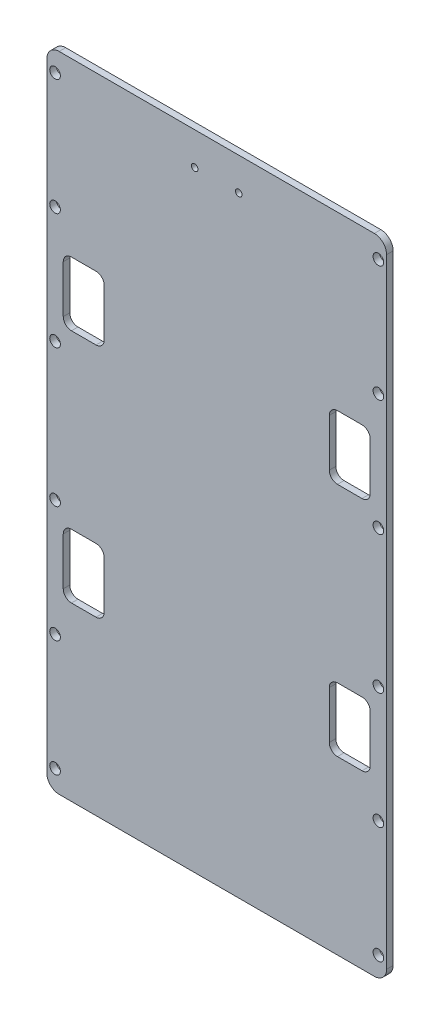
SolidWorks part; units mm, degrees
material "FR4_stuffedProtoboard"
ref_plane "Front Plane" through (0, 0, 0) normal (0, 0, 1) x (1, 0, 0)
ref_plane "Top Plane" through (0, 0, 0) normal (0, 1, 0) x (1, 0, 0)
ref_plane "Right Plane" through (0, 0, 0) normal (1, 0, 0) x (0, 0, -1)
sketch "Sketch1" plane through (0, 0, 0) normal (0, 0, 1) x (1, 0, 0)
  line L0 (-41.5, 0) -> (0, 0) construction
  line L1 (-38.5, 78.6) -> (38.5, 78.6)
  line L2 (-41.5, 75.6) -> (-41.5, -75.6)
  line L3 (-38.5, -78.6) -> (38.5, -78.6)
  line L4 (41.5, 75.6) -> (41.5, -75.6)
  line L5 (0, 0) -> (41.5, 0) construction
  line L6 (6.16, 74.2) -> (0, 70.6)
  line L7 (-35, 74.6) -> (-20.5, 74.6)
  line L8 (-37.5, 72.1) -> (-37.5, 52.1)
  line L9 (-35, 49.6) -> (-20.5, 49.6)
  line L10 (-18, 72.1) -> (-18, 52.1)
  line L11 (-12.5, 74.6) -> (12.5, 74.6)
  line L12 (-15, 72.1) -> (-15, 52.1)
  line L13 (-12.5, 49.6) -> (12.5, 49.6)
  line L14 (15, 72.1) -> (15, 52.1)
  line L15 (20.5, 74.6) -> (35, 74.6)
  line L16 (18, 72.1) -> (18, 52.1)
  line L17 (20.5, 49.6) -> (35, 49.6)
  line L18 (37.5, 72.1) -> (37.5, 52.1)
  line L19 (-35, 46.6) -> (-20.5, 46.6)
  line L20 (-37.5, 44.1) -> (-37.5, 21.1)
  line L21 (-35, 18.6) -> (-20.5, 18.6)
  line L22 (-18, 44.1) -> (-18, 21.1)
  line L23 (-12.5, 46.6) -> (12.5, 46.6)
  line L24 (-15, 44.1) -> (-15, 21.1)
  line L25 (-12.5, 18.6) -> (12.5, 18.6)
  line L26 (15, 44.1) -> (15, 21.1)
  line L27 (20.5, 46.6) -> (35, 46.6)
  line L28 (18, 44.1) -> (18, 21.1)
  line L29 (20.5, 18.6) -> (35, 18.6)
  line L30 (37.5, 44.1) -> (37.5, 21.1)
  line L31 (-35, 15.6) -> (-20.5, 15.6)
  line L32 (-37.5, 13.1) -> (-37.5, -13.1)
  line L33 (-35, -15.6) -> (-20.5, -15.6)
  line L34 (-18, 13.1) -> (-18, -13.1)
  line L35 (-12.5, 15.6) -> (12.5, 15.6)
  line L36 (-15, 13.1) -> (-15, -13.1)
  line L37 (-12.5, -15.6) -> (12.5, -15.6)
  line L38 (15, 13.1) -> (15, -13.1)
  line L39 (20.5, 15.6) -> (35, 15.6)
  line L40 (18, 13.1) -> (18, -13.1)
  line L41 (20.5, -15.6) -> (35, -15.6)
  line L42 (37.5, 13.1) -> (37.5, -13.1)
  line L43 (-35, -18.6) -> (-20.5, -18.6)
  line L44 (-37.5, -21.1) -> (-37.5, -44.1)
  line L45 (-35, -46.6) -> (-20.5, -46.6)
  line L46 (-18, -21.1) -> (-18, -44.1)
  line L47 (-12.5, -18.6) -> (12.5, -18.6)
  line L48 (-15, -21.1) -> (-15, -44.1)
  line L49 (-12.5, -46.6) -> (12.5, -46.6)
  line L50 (15, -21.1) -> (15, -44.1)
  line L51 (20.5, -18.6) -> (35, -18.6)
  line L52 (18, -21.1) -> (18, -44.1)
  line L53 (20.5, -46.6) -> (35, -46.6)
  line L54 (37.5, -21.1) -> (37.5, -44.1)
  line L55 (-35, -49.6) -> (-20.5, -49.6)
  line L56 (-37.5, -52.1) -> (-37.5, -72.1)
  line L57 (-35, -74.6) -> (-20.5, -74.6)
  line L58 (-18, -52.1) -> (-18, -72.1)
  line L59 (-12.5, -49.6) -> (12.5, -49.6)
  line L60 (-15, -52.1) -> (-15, -72.1)
  line L61 (-12.5, -74.6) -> (12.5, -74.6)
  line L62 (15, -52.1) -> (15, -72.1)
  line L63 (20.5, -49.6) -> (35, -49.6)
  line L64 (18, -52.1) -> (18, -72.1)
  line L65 (20.5, -74.6) -> (35, -74.6)
  line L66 (37.5, -52.1) -> (37.5, -72.1)
  line L67 (6.16, 74.2) -> (-6.16, 74.2)
  line L68 (6.16, 74.2) -> (6.16, 67)
  line L69 (6.16, 67) -> (-6.16, 67)
  line L70 (-6.16, 74.2) -> (-6.16, 67)
  line L71 (0, 70.6) -> (-6.16, 67)
  line L72 (6.16, 67) -> (0, 70.6)
  line L73 (0, 70.6) -> (-6.16, 74.2)
  arc A0 (-41.5, -75.6) -> (-38.5, -78.6) centre (-38.5, -75.6) ccw
  arc A1 (38.5, -78.6) -> (41.5, -75.6) centre (38.5, -75.6) ccw
  arc A2 (38.5, 78.6) -> (41.5, 75.6) centre (38.5, 75.6) cw
  arc A3 (-38.5, 78.6) -> (-41.5, 75.6) centre (-38.5, 75.6) ccw
  arc A4 (-20.5, 49.6) -> (-18, 52.1) centre (-20.5, 52.1) ccw
  arc A5 (-20.5, 74.6) -> (-18, 72.1) centre (-20.5, 72.1) cw
  arc A6 (-35, 74.6) -> (-37.5, 72.1) centre (-35, 72.1) ccw
  arc A7 (-20.5, -18.6) -> (-18, -21.1) centre (-20.5, -21.1) cw
  arc A8 (-35, -18.6) -> (-37.5, -21.1) centre (-35, -21.1) ccw
  arc A9 (-37.5, -44.1) -> (-35, -46.6) centre (-35, -44.1) ccw
  arc A10 (-20.5, -46.6) -> (-18, -44.1) centre (-20.5, -44.1) ccw
  arc A11 (-15, -44.1) -> (-12.5, -46.6) centre (-12.5, -44.1) ccw
  arc A12 (-12.5, -18.6) -> (-15, -21.1) centre (-12.5, -21.1) ccw
  arc A13 (12.5, -18.6) -> (15, -21.1) centre (12.5, -21.1) cw
  arc A14 (12.5, -46.6) -> (15, -44.1) centre (12.5, -44.1) ccw
  arc A15 (18, -44.1) -> (20.5, -46.6) centre (20.5, -44.1) ccw
  arc A16 (20.5, -18.6) -> (18, -21.1) centre (20.5, -21.1) ccw
  arc A17 (35, -18.6) -> (37.5, -21.1) centre (35, -21.1) cw
  arc A18 (35, -46.6) -> (37.5, -44.1) centre (35, -44.1) ccw
  arc A19 (35, -49.6) -> (37.5, -52.1) centre (35, -52.1) cw
  arc A20 (35, -74.6) -> (37.5, -72.1) centre (35, -72.1) ccw
  arc A21 (18, -72.1) -> (20.5, -74.6) centre (20.5, -72.1) ccw
  arc A22 (20.5, -49.6) -> (18, -52.1) centre (20.5, -52.1) ccw
  arc A23 (12.5, -49.6) -> (15, -52.1) centre (12.5, -52.1) cw
  arc A24 (12.5, -74.6) -> (15, -72.1) centre (12.5, -72.1) ccw
  arc A25 (-15, -72.1) -> (-12.5, -74.6) centre (-12.5, -72.1) ccw
  arc A26 (-12.5, -49.6) -> (-15, -52.1) centre (-12.5, -52.1) ccw
  arc A27 (-20.5, -49.6) -> (-18, -52.1) centre (-20.5, -52.1) cw
  arc A28 (-35, -49.6) -> (-37.5, -52.1) centre (-35, -52.1) ccw
  arc A29 (-37.5, -72.1) -> (-35, -74.6) centre (-35, -72.1) ccw
  arc A30 (-20.5, -74.6) -> (-18, -72.1) centre (-20.5, -72.1) ccw
  arc A31 (-37.5, -13.1) -> (-35, -15.6) centre (-35, -13.1) ccw
  arc A32 (-35, 15.6) -> (-37.5, 13.1) centre (-35, 13.1) ccw
  arc A33 (-20.5, 15.6) -> (-18, 13.1) centre (-20.5, 13.1) cw
  arc A34 (-20.5, -15.6) -> (-18, -13.1) centre (-20.5, -13.1) ccw
  arc A35 (-15, -13.1) -> (-12.5, -15.6) centre (-12.5, -13.1) ccw
  arc A36 (-12.5, 15.6) -> (-15, 13.1) centre (-12.5, 13.1) ccw
  arc A37 (12.5, 15.6) -> (15, 13.1) centre (12.5, 13.1) cw
  arc A38 (12.5, -15.6) -> (15, -13.1) centre (12.5, -13.1) ccw
  arc A39 (18, -13.1) -> (20.5, -15.6) centre (20.5, -13.1) ccw
  arc A40 (35, -15.6) -> (37.5, -13.1) centre (35, -13.1) ccw
  arc A41 (20.5, 15.6) -> (18, 13.1) centre (20.5, 13.1) ccw
  arc A42 (35, 15.6) -> (37.5, 13.1) centre (35, 13.1) cw
  arc A43 (35, 18.6) -> (37.5, 21.1) centre (35, 21.1) ccw
  arc A44 (18, 21.1) -> (20.5, 18.6) centre (20.5, 21.1) ccw
  arc A45 (20.5, 46.6) -> (18, 44.1) centre (20.5, 44.1) ccw
  arc A46 (35, 46.6) -> (37.5, 44.1) centre (35, 44.1) cw
  arc A47 (35, 49.6) -> (37.5, 52.1) centre (35, 52.1) ccw
  arc A48 (35, 74.6) -> (37.5, 72.1) centre (35, 72.1) cw
  arc A49 (18, 52.1) -> (20.5, 49.6) centre (20.5, 52.1) ccw
  arc A50 (20.5, 74.6) -> (18, 72.1) centre (20.5, 72.1) ccw
  arc A51 (12.5, 49.6) -> (15, 52.1) centre (12.5, 52.1) ccw
  arc A52 (12.5, 74.6) -> (15, 72.1) centre (12.5, 72.1) cw
  arc A53 (-12.5, 74.6) -> (-15, 72.1) centre (-12.5, 72.1) ccw
  arc A54 (-15, 52.1) -> (-12.5, 49.6) centre (-12.5, 52.1) ccw
  arc A55 (12.5, 18.6) -> (15, 21.1) centre (12.5, 21.1) ccw
  arc A56 (12.5, 46.6) -> (15, 44.1) centre (12.5, 44.1) cw
  arc A57 (-12.5, 46.6) -> (-15, 44.1) centre (-12.5, 44.1) ccw
  arc A58 (-15, 21.1) -> (-12.5, 18.6) centre (-12.5, 21.1) ccw
  arc A59 (-37.5, 21.1) -> (-35, 18.6) centre (-35, 21.1) ccw
  arc A60 (-20.5, 18.6) -> (-18, 21.1) centre (-20.5, 21.1) ccw
  arc A61 (-20.5, 46.6) -> (-18, 44.1) centre (-20.5, 44.1) cw
  arc A62 (-35, 46.6) -> (-37.5, 44.1) centre (-35, 44.1) ccw
  arc A63 (-37.5, 52.1) -> (-35, 49.6) centre (-35, 52.1) ccw
  circle A64 centre (0, 70.6) radius 0.5953
  point P72 (41.5, -78.6)
  point P75 (41.5, 78.6)
  point P78 (-41.5, 78.6)
  point P159 (37.5, 18.6)
  point P166 (37.5, 46.6)
  point P169 (37.5, 49.6)
  point P172 (37.5, 74.6)
  point P181 (15, 74.6)
  point P184 (-15, 74.6)
  dimension "D16" = 3
  dimension "D17" = 2.5
  dimension "D18" = 2.5
  dimension "D23" = 1.1906
  dimension "D1" = 3
  dimension "D2" = 3
  dimension "D3" = 3
  dimension "D4" = 3
  dimension "D5" = 3
  dimension "D6" = 3
  dimension "D7" = 4
  dimension "D8" = 4
  dimension "D9" = 4
  dimension "D10" = 4
  dimension "D11" = 157.2
  dimension "D12" = 83
  dimension "D13" = 30
  dimension "D14" = 25
  dimension "D15" = 28
  dimension "D19" = 0.4
  dimension "D20" = 8.84
  dimension "D21" = 8.84
  dimension "D22" = 7.2
extrude "General Shape" add sketch "Sketch1" along normal blind 1.6 contours L8 A63 L9 A4 L10 A5 L7 A6 | L12 A54 L13 A51 L14 A52 L11 A53 | L15 A50 L16 A49 L17 A47 L18 A48 | L1 A3 L2 A0 L3 A1 L4 A2 A63 L8 A6 L7 A5 L10 A4 L9 A62 L19 A61 L22 A60 L21 A59 L20 A58 L24 A57 L23 A56 L26 A55 L25 A54 L12 A53 L11 A52 L14 A51 L13 A50 L15 A48 L18 A47 L17 | L24 A58 L25 A55 L26 A56 L23 A57 | L19 A62 L20 A59 L21 A60 L22 A61 | A46 L27 A45 L28 A44 L29 A43 L30 | A42 L39 A41 L40 A39 L41 A40 L42 | L37 A38 L38 A37 L35 A36 L36 A35 | L33 A34 L34 A33 L31 A32 L32 A31 | L45 A10 L46 A7 L43 A8 L44 A9 | L49 A14 L50 A13 L47 A12 L48 A11 | L53 A18 L54 A17 L51 A16 L52 A15 | L63 A22 L64 A21 L65 A20 L66 A19 | L59 A26 L60 A25 L61 A24 L62 A23 | L57 A30 L58 A27 L55 A28 L56 A29 | A64 L72 L68 L6 | A64 L6 L67 L73 | A64 L73 L70 L71 | A64 L71 L69 L72 | L6 A64 L73 | L72 A64 L6 | L71 A64 L72 | L73 A64 L71
sketch "Sketch2" plane through (0, 0, 0) normal (0, 0, -1) x (-1, 0, 0)
  line L0 (38.5, 78.6) -> (-38.5, 78.6) construction
  line L1 (-22, 64) -> (0, 64) construction
  line L2 (-41.5, 75.6) -> (-41.5, -75.6) construction
  line L3 (-22, 64) -> (-22, 54) construction
  line L4 (-22, -71.6) -> (0, -71.6) construction
  line L5 (-22, -71.6) -> (-22, -61.6) construction
  line L7 (38.5, -78.6) -> (-38.5, -78.6) construction
  line L8 (-41.5, 75.6) -> (-41.5, -75.6) construction
  circle A0 centre (-22, 64) radius 1.2
  circle A1 centre (0, 64) radius 1.2
  circle A2 centre (22, 64) radius 1.2
  circle A3 centre (0, 54) radius 1.2
  circle A4 centre (22, 54) radius 1.2
  circle A5 centre (0, 44) radius 1.2
  circle A6 centre (22, 44) radius 1.2
  circle A7 centre (0, 34) radius 1.2
  circle A8 centre (22, 34) radius 1.2
  circle A9 centre (0, 24) radius 1.2
  circle A10 centre (22, 24) radius 1.2
  circle A11 centre (-22, 54) radius 1.2
  circle A12 centre (-22, 44) radius 1.2
  circle A13 centre (-22, 34) radius 1.2
  circle A14 centre (-22, 24) radius 1.2
  circle A15 centre (-22, -71.6) radius 1.2
  circle A16 centre (0, -71.6) radius 1.2
  circle A17 centre (22, -71.6) radius 1.2
  circle A18 centre (0, -61.6) radius 1.2
  circle A19 centre (22, -61.6) radius 1.2
  circle A20 centre (0, -51.6) radius 1.2
  circle A21 centre (22, -51.6) radius 1.2
  circle A22 centre (0, -41.6) radius 1.2
  circle A23 centre (22, -41.6) radius 1.2
  circle A24 centre (0, -31.6) radius 1.2
  circle A25 centre (22, -31.6) radius 1.2
  circle A26 centre (0, -21.6) radius 1.2
  circle A27 centre (22, -21.6) radius 1.2
  circle A28 centre (-22, -61.6) radius 1.2
  circle A29 centre (-22, -51.6) radius 1.2
  circle A30 centre (-22, -41.6) radius 1.2
  circle A31 centre (-22, -31.6) radius 1.2
  circle A32 centre (-22, -21.6) radius 1.2
  dimension "D3" = 2.4
  dimension "D9" = 2.4
  dimension "D1" = 14.6
  dimension "D2" = 19.5
  dimension "D6" = 90
  dimension "D7" = 22
  dimension "D8" = 10
  dimension "D10" = 7
  dimension "D11" = 19.5
  dimension "D14" = 90
  dimension "D15" = 22
  dimension "D16" = 10
  dimension "D4" = 3
  dimension "D5" = 5
  dimension "D12" = 3
  dimension "D13" = 6
hole_wizard "M2 Clearance Hole1" positions "3DSketch1" profile "Sketch4" hole size "M2" standard "ANSI Metric" end condition up to next
sketch3d "3DSketch1"
  line L0 (-39.5, 73.6, 0) -> (-39.5, 45.2, 0) construction
  line L1 (-39.5, 45.2, 0) -> (-39.5, 16.8, 0) construction
  line L3 (-41.5, 75.6, 0) -> (-41.5, -75.6, 0) construction
  line L4 (-38.5, 78.6, 0) -> (38.5, 78.6, 0) construction
  point P0 (-39.5, 73.6, 0)
  point P2 (-39.5, 45.2, 0)
  point P4 (-39.5, 16.8, 0)
  dimension "D1" = 2
  dimension "D2" = 5
  dimension "D3" = 28.4
sketch "Sketch4" plane through (-39.5, 73.6, 0) normal (1, 0, 0) x (0, 1, 0)
  line L0 (0, 0) -> (0, 1.6)
  line L1 (0, 1.6) -> (1.3, 1.6)
  line L2 (1.3, 1.6) -> (1.3, 0)
  line L5 (1.3, 0) -> (0, 0)
  line L11 (0, -6.35) -> (0, 107.95) construction
  dimension "Thru Hole Dia." = 2.6
  dimension "Thru Hole Depth" = 1.6
mirror "Mirror1" about plane through (0, 0, 0) normal (1, 0, 0) of "M2 Clearance Hole1"
mirror "Mirror2" about plane through (0, 0, 0) normal (0, 1, 0) of "Mirror1", "M2 Clearance Hole1"
sketch "Sketch5" plane through (0, 0, 0) normal (0, 0, -1) x (-1, 0, 0)
  line L0 (12.5, 74.6) -> (-12.5, 74.6) construction
  line L1 (-5, 73.6) -> (5, 73.6)
  line L2 (-7.5, 71.1) -> (-7.5, 70.1)
  line L3 (-5, 67.6) -> (5, 67.6)
  line L4 (7.5, 71.1) -> (7.5, 70.1)
  line L5 (15, 72.1) -> (15, 52.1) construction
  line L6 (-7, 68.6) -> (7, 68.6)
  arc A0 (5, 73.6) -> (7.5, 71.1) centre (5, 71.1) cw
  arc A1 (5, 67.6) -> (7.5, 70.1) centre (5, 70.1) ccw
  arc A2 (-7.5, 70.1) -> (-5, 67.6) centre (-5, 70.1) ccw
  arc A3 (-5, 73.6) -> (-7.5, 71.1) centre (-5, 71.1) ccw
  circle A4 centre (-5.38, 70.6) radius 0.8
  circle A5 centre (5.38, 70.6) radius 0.8
  point P6 (7.5, 73.6)
  point P9 (7.5, 67.6)
  point P14 (-7.5, 73.6)
  dimension "D3" = 2.5
  dimension "D5" = 1.6
  dimension "D6" = 2.12
  dimension "D1" = 6
  dimension "D2" = 15
  dimension "D4" = 1
  dimension "D7" = 2.12
  dimension "D8" = 7.5
  dimension "D9" = 3
  dimension "D10" = 3
  dimension "D11" = 14
extrude "Connector holes" cut sketch "Sketch5" against normal through all contours A4 | A5
sketch "Sketch6" plane through (0, 0, 0) normal (0, 0, -1) x (-1, 0, 0)
  line L0 (38.5, -78.6) -> (-38.5, -78.6) construction
  line L1 (-35.5, 36.6) -> (-29.5, 36.6)
  line L2 (-37.5, 34.6) -> (-37.5, 23)
  line L3 (-35.5, 21) -> (-29.5, 21)
  line L4 (-27.5, 34.6) -> (-27.5, 23)
  line L5 (29.5, 36.6) -> (35.5, 36.6)
  line L6 (27.5, 34.6) -> (27.5, 23)
  line L7 (29.5, 21) -> (35.5, 21)
  line L8 (37.5, 34.6) -> (37.5, 23)
  line L9 (-35.5, -21) -> (-29.5, -21)
  line L10 (-37.5, -23) -> (-37.5, -34.6)
  line L11 (-35.5, -36.6) -> (-29.5, -36.6)
  line L12 (-27.5, -23) -> (-27.5, -34.6)
  line L13 (29.5, -21) -> (35.5, -21)
  line L14 (27.5, -23) -> (27.5, -34.6)
  line L15 (29.5, -36.6) -> (35.5, -36.6)
  line L16 (37.5, -23) -> (37.5, -34.6)
  line L17 (38.5, 78.6) -> (-38.5, 78.6) construction
  line L18 (-41.5, 75.6) -> (-41.5, -75.6) construction
  line L19 (41.5, 75.6) -> (41.5, -75.6) construction
  arc A0 (-37.5, 23) -> (-35.5, 21) centre (-35.5, 23) ccw
  arc A1 (-29.5, 21) -> (-27.5, 23) centre (-29.5, 23) ccw
  arc A2 (-29.5, 36.6) -> (-27.5, 34.6) centre (-29.5, 34.6) cw
  arc A3 (-35.5, 36.6) -> (-37.5, 34.6) centre (-35.5, 34.6) ccw
  arc A4 (-37.5, -34.6) -> (-35.5, -36.6) centre (-35.5, -34.6) ccw
  arc A5 (-29.5, -36.6) -> (-27.5, -34.6) centre (-29.5, -34.6) ccw
  arc A6 (-29.5, -21) -> (-27.5, -23) centre (-29.5, -23) cw
  arc A7 (-35.5, -21) -> (-37.5, -23) centre (-35.5, -23) ccw
  arc A8 (27.5, -34.6) -> (29.5, -36.6) centre (29.5, -34.6) ccw
  arc A9 (35.5, -21) -> (37.5, -23) centre (35.5, -23) cw
  arc A10 (29.5, -21) -> (27.5, -23) centre (29.5, -23) ccw
  arc A11 (35.5, -36.6) -> (37.5, -34.6) centre (35.5, -34.6) ccw
  arc A12 (35.5, 21) -> (37.5, 23) centre (35.5, 23) ccw
  arc A13 (35.5, 36.6) -> (37.5, 34.6) centre (35.5, 34.6) cw
  arc A14 (29.5, 36.6) -> (27.5, 34.6) centre (29.5, 34.6) ccw
  arc A15 (27.5, 23) -> (29.5, 21) centre (29.5, 23) ccw
  dimension "D7" = 2
  dimension "D8" = 2
  dimension "D9" = 2
  dimension "D10" = 2
  dimension "D11" = 2
  dimension "D1" = 42
  dimension "D2" = 42
  dimension "D3" = 4
  dimension "D4" = 10
  dimension "D5" = 4
  dimension "D6" = 42
extrude "Star Tracker Cutouts" cut sketch "Sketch6" against normal through all
sketch "Sketch7" plane through (0, 0, 1.6) normal (0, 0, 1) x (1, 0, 0)
  line L0 (-38.5, 78.6) -> (38.5, 78.6) construction
  line L1 (-34.8625, 77.6) -> (34.8625, 77.6)
  line L2 (-34.8625, 77.6) -> (-34.8625, 37.6)
  line L3 (-34.8625, 37.6) -> (34.8625, 37.6)
  line L4 (34.8625, 77.6) -> (34.8625, 37.6)
  line L5 (-41.5, 75.6) -> (-41.5, -75.6) construction
  line L6 (-34.8625, 20) -> (-34.8625, -20)
  line L7 (-34.8625, 20) -> (34.8625, 20)
  line L8 (34.8625, 20) -> (34.8625, -20)
  line L9 (-34.8625, -20) -> (34.8625, -20)
  line L10 (-34.8625, -37.6) -> (-34.8625, -77.6)
  line L11 (-34.8625, -37.6) -> (34.8625, -37.6)
  line L12 (34.8625, -37.6) -> (34.8625, -77.6)
  line L13 (-34.8625, -77.6) -> (34.8625, -77.6)
  line L14 (-34.8625, 77.6) -> (-34.8625, 20) construction
  dimension "D1" = 40
  dimension "D2" = 69.725
  dimension "D3" = 1
  dimension "D4" = 6.6375
  dimension "D6" = 57.6
  dimension "D5" = 3
